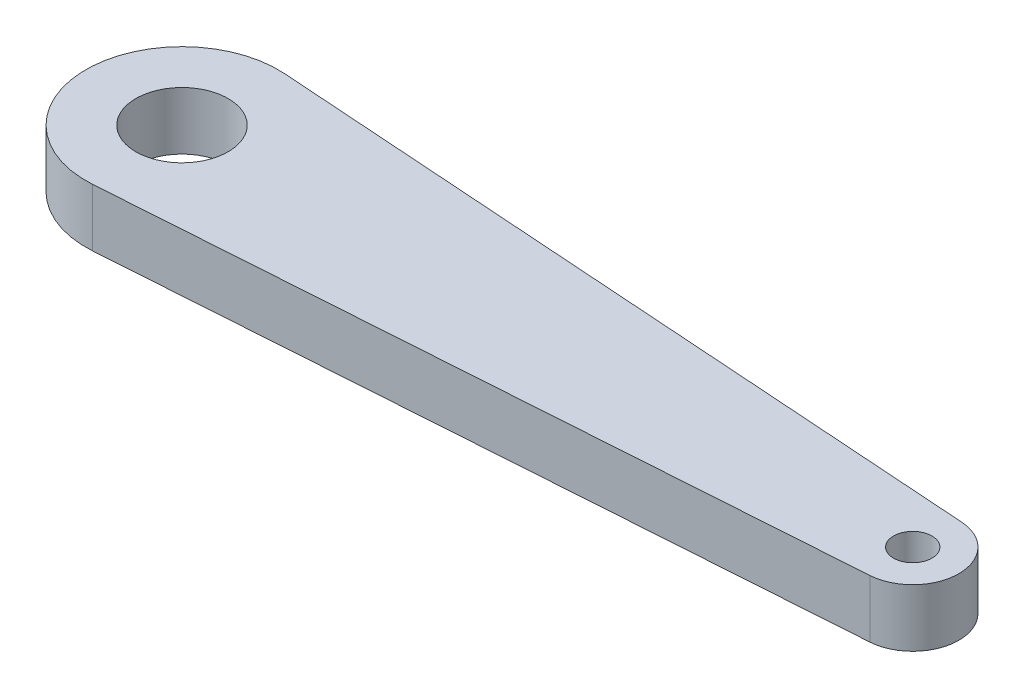
SolidWorks part; units mm, degrees
ref_plane "Front Plane" through (0, 0, 0) normal (0, 0, 1) x (1, 0, 0)
ref_plane "Top Plane" through (0, 0, 0) normal (0, 1, 0) x (1, 0, 0)
ref_plane "Right Plane" through (0, 0, 0) normal (1, 0, 0) x (0, 0, -1)
sketch "Sketch2" plane through (0, 0, 0) normal (0, 1, 0) x (1, 0, 0)
  line L0 (-36.4106, 0) -> (77.0894, 0) construction
  line L1 (-23.0553, 12.4707) -> (71.4999, 5.9859)
  line L2 (-23.0553, -12.4707) -> (71.4999, -5.9859)
  circle A0 centre (71.0894, 0) radius 2.5
  arc A1 (71.4999, -5.9859) -> (71.4999, 5.9859) centre (71.0894, 0) ccw
  arc A2 (-23.0553, 12.4707) -> (-23.0553, -12.4707) centre (-23.9106, 0) ccw
  circle A3 centre (-23.9106, 0) radius 6
  dimension "D1" = 12
  dimension "D2" = 5
  dimension "D3" = 25
  dimension "D5" = 12
  dimension "D4" = 95
extrude "Boss-Extrude1" add sketch "Sketch2" along normal blind 7.5
